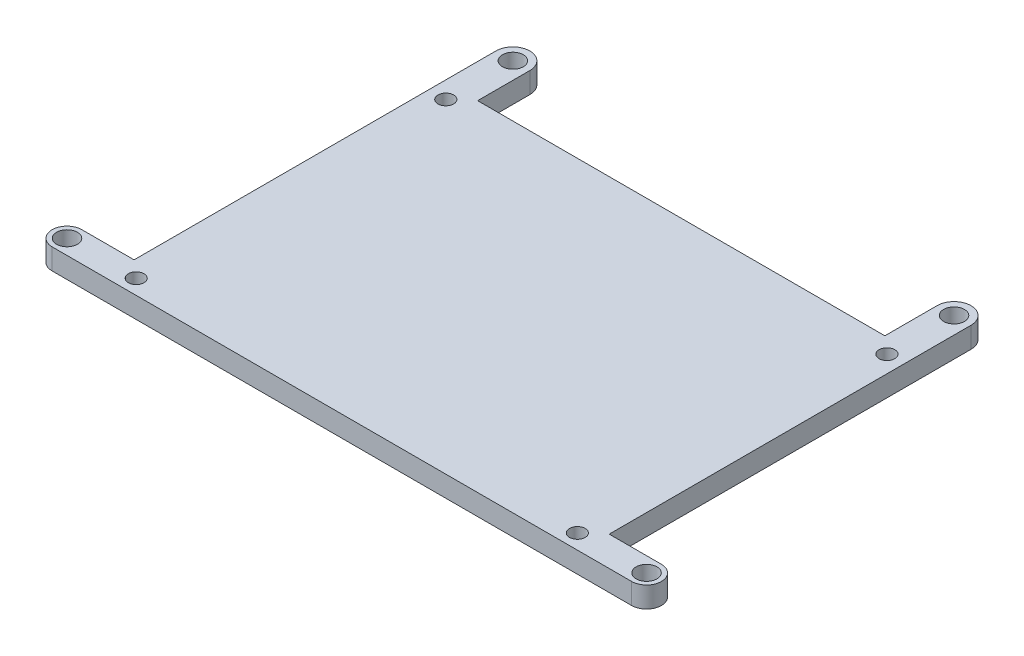
SolidWorks part; units mm, degrees
ref_plane "Front Plane" through (0, 0, 0) normal (0, 0, 1) x (1, 0, 0)
ref_plane "Top Plane" through (0, 0, 0) normal (0, 1, 0) x (1, 0, 0)
ref_plane "Right Plane" through (0, 0, 0) normal (1, 0, 0) x (0, 0, -1)
sketch "Sketch1" plane through (0, 0, 0) normal (0, 1, 0) x (1, 0, 0)
  line L0 (-50.4947, 0) -> (55.5, 0) construction
  line L1 (-45.5, 32.5) -> (-42.25, 32.5) construction
  line L2 (-45.5, 32.5) -> (-45.5, -26.8)
  line L3 (-45.5, -32.5) -> (45.5, -32.5)
  line L4 (45.5, 32.5) -> (45.5, -26.8)
  line L5 (-45.5, 32.5) -> (45.5, -32.5) construction
  line L6 (-45.5, -32.5) -> (45.5, 32.5) construction
  line L7 (0, -40.6779) -> (0, 40.2245) construction
  line L8 (-42.25, 19.7722) -> (-42.25, 46.2439) construction
  line L9 (42.25, 19.7722) -> (42.25, 46.2439) construction
  line L10 (-45.5, 32.5) -> (-45.5, 42.5)
  line L11 (-39, 42.5) -> (-39, 32.5)
  line L12 (-42.25, 32.5) -> (-39, 32.5) construction
  line L13 (-39, 32.5) -> (39, 32.5)
  line L14 (45.5, 32.5) -> (45.5, 42.5)
  line L15 (39, 42.5) -> (39, 32.5)
  line L16 (39, 32.5) -> (42.25, 32.5) construction
  line L17 (42.25, 32.5) -> (45.5, 32.5) construction
  line L18 (-45.5, -32.5) -> (-55.5, -32.5)
  line L19 (-55.5, -26.8) -> (-45.5, -26.8)
  line L20 (-63.7583, -29.65) -> (60.8171, -29.65) construction
  line L21 (-55.5, -32.5) -> (-45.5, -32.5)
  line L22 (55.5, -26.8) -> (45.5, -26.8)
  line L23 (45.5, -32.5) -> (55.5, -32.5)
  line L24 (45.5, -26.8) -> (45.5, -29.65) construction
  line L25 (45.5, -29.65) -> (45.5, -32.5) construction
  line L26 (-45.5, -26.8) -> (-45.5, -29.65) construction
  line L27 (-45.5, -29.65) -> (-45.5, -32.5) construction
  circle A0 centre (-42.25, 29.65) radius 1.5
  circle A1 centre (42.25, 29.65) radius 1.5
  circle A2 centre (42.25, -29.65) radius 1.5
  circle A3 centre (-42.25, -29.65) radius 1.5
  arc A4 (-45.5, 42.5) -> (-39, 42.5) centre (-42.25, 42.5) cw
  circle A5 centre (-42.25, 42.5) radius 2
  circle A6 centre (42.25, 42.5) radius 2
  arc A7 (45.5, 42.5) -> (39, 42.5) centre (42.25, 42.5) ccw
  arc A8 (-55.5, -32.5) -> (-55.5, -26.8) centre (-55.5, -29.65) cw
  circle A9 centre (-55.5, -29.65) radius 2
  circle A10 centre (55.5, -29.65) radius 2
  arc A11 (55.5, -32.5) -> (55.5, -26.8) centre (55.5, -29.65) ccw
  point P0 (0, 0)
  point P47 (-50.4947, 0)
  point P48 (0, -40.6779)
  point P49 (0, 40.2245)
  point P50 (55.5, 0)
  point P52 (60.8171, -29.65)
  dimension "D3" = 84.5
  dimension "D5" = 3
  dimension "D6" = 3.25
  dimension "D7" = 4
  dimension "D9" = 10
  dimension "D10" = 4
  dimension "D1" = 65
  dimension "D2" = 91
  dimension "D4" = 2.85
  dimension "D8" = 10
extrude "Boss-Extrude1" add sketch "Sketch1" along normal mid plane 4 contours L23 A11 L22 L4 L14 A7 L15 L13 L11 A4 L10 L2 L3 A10 A3 A2 A0 A1 A5 A6 | A8 L18 L2 L19 A9
